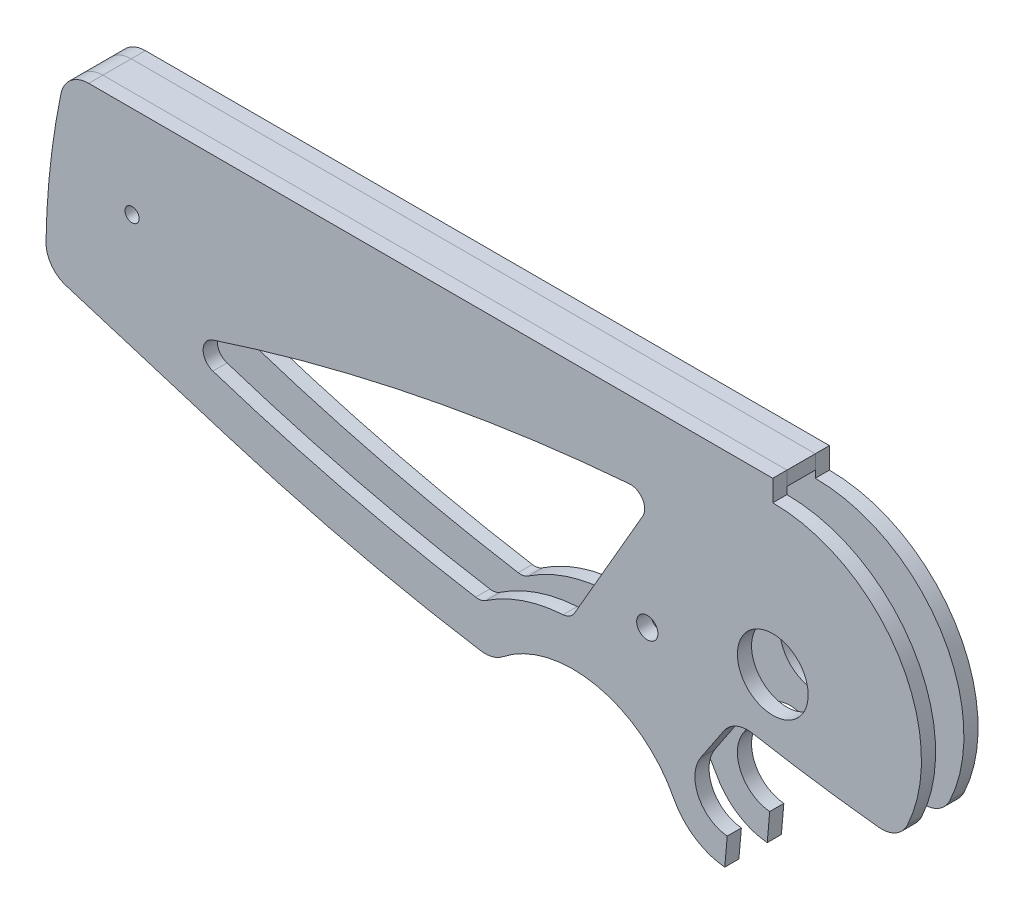
SolidWorks part; units mm, degrees
material "Obyčejná uhlíková ocel"
ref_plane "Přední rovina" through (0, 0, 0) normal (0, 0, 1) x (1, 0, 0)
ref_plane "Horní rovina" through (0, 0, 0) normal (0, 1, 0) x (1, 0, 0)
ref_plane "Pravá rovina" through (0, 0, 0) normal (1, 0, 0) x (0, 0, -1)
sketch "Skica15" plane through (0, 0, 0) normal (0, 0, 1) x (1, 0, 0)
  line L0 (0, 10) -> (0, -10)
  line L1 (0, 0) -> (-50, 0) construction
  line L2 (-1.7365, -9.8481) -> (1.7365, 9.8481)
  line L3 (0, 0) -> (49.2404, -8.6824) construction
  arc A0 (-50, 0) -> (0, 10) centre (0, -120) cw
  arc A1 (-50, 0) -> (0, -10) centre (0, 120) ccw
  arc A2 (1.7365, 9.8481) -> (49.2404, -8.6824) centre (-20.8378, -118.1769) cw
  arc A3 (-1.7365, -9.8481) -> (49.2404, -8.6824) centre (20.8378, 118.1769) ccw
  circle A4 centre (0, 0) radius 10
  dimension "D2" = 130
  dimension "D1" = 20
  dimension "D3" = 50
  dimension "D4" = 10
ref_plane "Rovina2" through (0, 0, 1) normal (0, 0, 1) x (1, 0, 0)
sketch "Skica1" plane through (0, 0, 1) normal (0, 0, 1) x (1, 0, 0)
  line L1 (-3.4519, -5.1731) -> (-5.0795, -7.6124)
  line L2 (0, 0) -> (-59.5409, 0) construction
  line L3 (-3, -9) -> (-3, -17.0212) construction
  line L4 (-3.2179, -11.4905) -> (-3.3922, -13.4829)
  line L5 (-49.9157, -1.1721) -> (-38.4483, -4.7076)
  line L6 (0, 10.5) -> (0, 12)
  line L7 (0, 12) -> (-48.3078, 12)
  circle A0 centre (0, 0) radius 2.5
  arc A1 (9.5026, -4.4665) -> (0, 10.5) centre (0, 0) ccw
  arc A2 (7.478, -5.6042) -> (-1.4305, -4.3154) centre (20.8378, 118.1769) cw
  arc A3 (-5.0795, -7.6124) -> (-3.2179, -11.4905) centre (-3, -9) ccw
  arc A4 (-7, -11.0616) -> (-3.3922, -13.4829) centre (-3, -9) ccw
  arc A5 (7.478, -5.6042) -> (9.5026, -4.4665) centre (7.6926, -3.6157) ccw
  arc A6 (-50.2663, 10.4054) -> (-51.3262, 0.7691) centre (0, 0) ccw
  arc A7 (-1.7365, -9.8481) -> (49.2404, -8.6824) centre (20.8378, 118.1769) ccw construction
  arc A8 (-7, -11.0616) -> (-19.0746, -8.4525) centre (-14.1111, -14.7265) ccw
  arc A9 (-51.3262, 0.7691) -> (-49.9157, -1.1721) centre (-49.3265, 0.7391) ccw
  arc A10 (-20.6316, -8.8588) -> (-38.4483, -4.7076) centre (0, 120) cw
  circle A11 centre (-50, 0) radius 1 construction
  arc A12 (-20.6316, -8.8588) -> (-19.0746, -8.4525) centre (-20.3154, -6.8839) ccw
  arc A13 (-50, 0) -> (0, -10) centre (0, 120) ccw construction
  arc A14 (-1.4305, -4.3154) -> (-3.4519, -5.1731) centre (-1.7882, -6.2832) ccw
  arc A15 (-48.3078, 12) -> (-50.2663, 10.4054) centre (-48.3078, 10) ccw
  point P34 (-19.7017, -9.0042)
  dimension "D1" = 5
  dimension "D2" = 10.5
  dimension "D3" = 2
  dimension "D4" = 5
  dimension "D5" = 3
  dimension "D6" = 9
  dimension "D7" = 2
  dimension "D10" = 2
  dimension "D11" = 2
  dimension "D13" = 2
  dimension "D14" = 12
  dimension "D12" = 2
  dimension "D9" = 0.5
  dimension "D16" = 8
  dimension "D17" = 1.5
  dimension "D19" = 2
  dimension "D15" = 2
  dimension "D8" = 5
  dimension "D18" = 7
extrude "Přidat vysunutím1" add sketch "Skica1" along normal blind 1
sketch "Skica2" plane through (0, 0, 0) normal (0, 0, 1) x (1, 0, 0)
  line L0 (-8.8633, -1.5628) -> (0, 0) construction
  line L2 (0, 0) -> (-50, 0) construction
  circle A0 centre (-8.8633, -1.5628) radius 0.75
  circle A1 centre (-45.2466, 5.5) radius 0.5
  dimension "D3" = 1.5
  dimension "D5" = 1
  dimension "D8" = 5.5
  dimension "D1" = 10
  dimension "D2" = 9
  dimension "D7" = 45.2466
sketch "Skica14" plane through (0, 0, 0) normal (0, 0, 1) x (1, 0, 0)
  line L0 (-14.001, -3.2504) -> (-9.1805, 5.0988)
  line L1 (0, 0) -> (-50, 0) construction
  arc A0 (-39.5409, -1.2137) -> (-20.9819, -5.7617) centre (0, 120) ccw
  arc A1 (-39.5422, 0.6873) -> (-10.1263, 6.5956) centre (0, -120) cw
  arc A2 (-38.4483, -4.7076) -> (-20.6316, -8.8588) centre (0, 120) ccw construction
  circle A3 centre (0, 0) radius 10 construction
  arc A4 (-39.5422, 0.6873) -> (-39.5409, -1.2137) centre (-39.2308, -0.263) ccw
  arc A5 (-20.2585, -5.6046) -> (-20.9819, -5.7617) centre (-20.8174, -4.7753) cw
  arc A6 (-9.1805, 5.0988) -> (-10.1263, 6.5956) centre (-10.0466, 5.5988) ccw
  arc A7 (0, 10) -> (-50, 0) centre (0, -120) ccw construction
  arc A8 (-20.2585, -5.6046) -> (-14.804, -3.7484) centre (-14.1111, -14.7265) cw
  arc A10 (-14.804, -3.7484) -> (-14.001, -3.2504) centre (-14.867, -2.7504) ccw
  arc A11 (-38.4483, -4.7076) -> (-20.6316, -8.8588) centre (0, 120) ccw construction
  arc A13 (-7, -11.0616) -> (-19.0746, -8.4525) centre (-14.1111, -14.7265) ccw construction
  dimension "D2" = 3
  dimension "D3" = 2
  dimension "D4" = 3
  dimension "D5" = 3
  dimension "D6" = 0.5
  dimension "D1" = 60
extrude "Odebrat vysunutím3" cut sketch "Skica14" along normal through all
extrude "Odebrat vysunutím2" cut sketch "Skica2" along normal through all
sketch "Skica16" plane through (0, 0, 0) normal (0, 0, -1) x (-1, 0, 0)
  line L0 (0, 12) -> (48.3078, 12) construction
  line L1 (0, 10.5) -> (0, 12) construction
  line L2 (0, 12) -> (48.3078, 12)
  line L3 (0, 11) -> (0, 12)
  arc A0 (51.3262, 0.7691) -> (50.2663, 10.4054) centre (0, 0) ccw construction
  arc A1 (49.9157, -1.1721) -> (51.3262, 0.7691) centre (49.3265, 0.7391) ccw construction
  arc A2 (50.2663, 10.4054) -> (48.3078, 12) centre (48.3078, 10) ccw construction
  arc A3 (51.3262, 0.7691) -> (50.2663, 10.4054) centre (0, 0) ccw
  arc A4 (51.3156, 0.531) -> (51.3262, 0.7691) centre (49.3265, 0.7391) ccw
  arc A5 (50.2663, 10.4054) -> (48.3078, 12) centre (48.3078, 10) ccw
  arc A13 (50.3846, 0.9231) -> (0, 11) centre (0, -120) ccw
  arc A14 (51.3156, 0.531) -> (0, 11) centre (0, -120) ccw
  dimension "D1" = 1
extrude "Přidat vysunutím2" add sketch "Skica16" along normal mid plane 2 separate body
mirror "Zrcadlit1" about plane through (0, 0, 0) normal (0, 0, 1) of bodies 119
